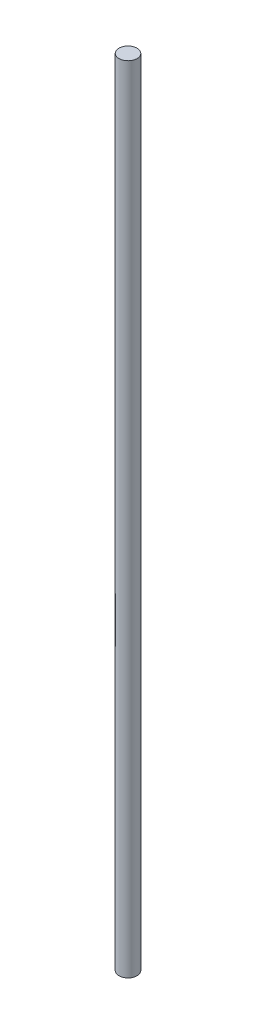
SolidWorks part; units mm, degrees
ref_plane "Front Plane" through (0, 0, 0) normal (0, 0, 1) x (1, 0, 0)
ref_plane "Top Plane" through (0, 0, 0) normal (0, 1, 0) x (1, 0, 0)
ref_plane "Right Plane" through (0, 0, 0) normal (1, 0, 0) x (0, 0, -1)
sketch "Sketch1" plane through (0, 0, 0) normal (0, 0, 1) x (1, 0, 0)
  line L1 (0, 0) -> (5, 0)
  line L2 (0, 0) -> (0, 439.4)
  line L3 (0, 439.4) -> (5, 439.4)
  line L4 (5, 0) -> (5, 439.4)
  dimension "D1" = 5
  dimension "D2" = 439.4
revolve "Revolve1" add sketch "Sketch1" angle 360 about L2
